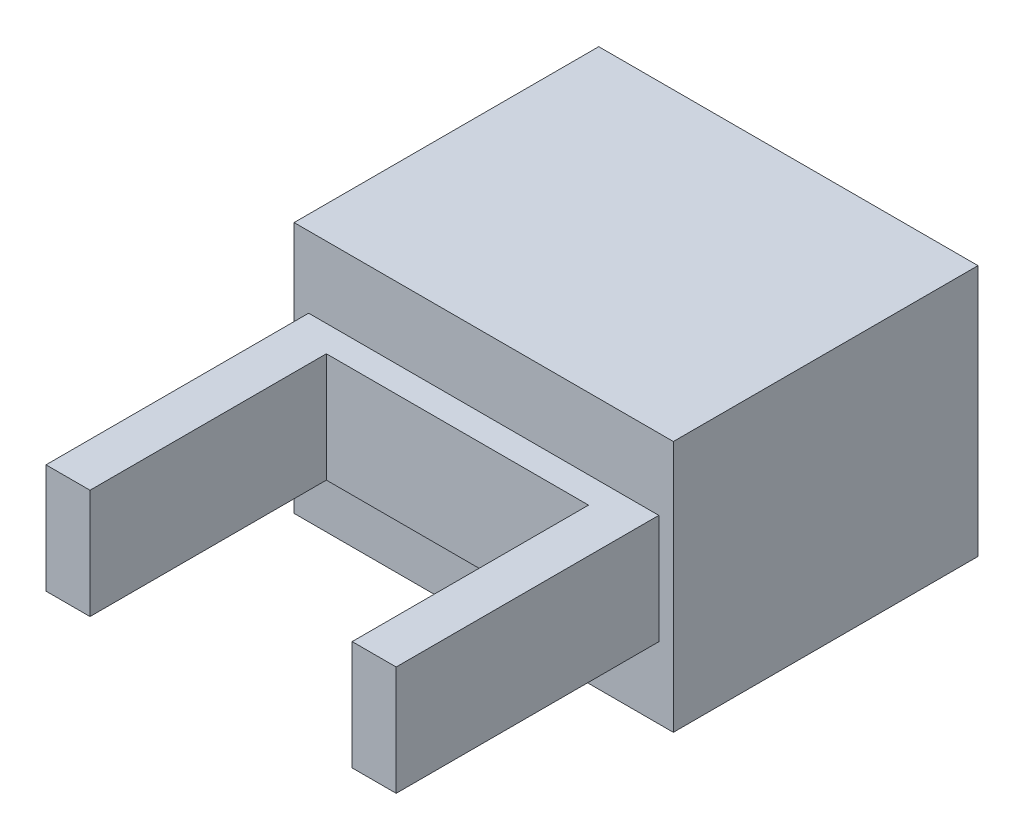
SolidWorks part; units mm, degrees
ref_plane "Front Plane" through (0, 0, 0) normal (0, 0, 1) x (1, 0, 0)
ref_plane "Top Plane" through (0, 0, 0) normal (0, 1, 0) x (1, 0, 0)
ref_plane "Right Plane" through (0, 0, 0) normal (1, 0, 0) x (0, 0, -1)
sketch "Sketch1" plane through (0, 0, 0) normal (0, 0, 1) x (1, 0, 0)
  line L1 (50.8, -15.875) -> (-50.8, -15.875)
  line L2 (50.8, -15.875) -> (50.8, 15.875)
  line L3 (50.8, 15.875) -> (-50.8, 15.875)
  line L4 (-50.8, -15.875) -> (-50.8, 15.875)
  line L5 (50.8, -15.875) -> (-50.8, 15.875) construction
  line L6 (50.8, 15.875) -> (-50.8, -15.875) construction
  point P0 (0, 0)
  dimension "D1" = 101.6
  dimension "D2" = 31.75
extrude "Boss-Extrude1" add sketch "Sketch1" along normal blind 76.2
sketch "Sketch2" plane through (0, 0, 76.2) normal (0, 0, 1) x (1, 0, 0)
  line L0 (50.8, 15.875) -> (-50.8, 15.875) construction
  line L1 (38.032, -15.875) -> (-38.032, -15.875)
  line L2 (38.032, -15.875) -> (38.032, 15.875)
  line L3 (38.032, 15.875) -> (-38.032, 15.875)
  line L4 (-38.032, -15.875) -> (-38.032, 15.875)
  line L5 (38.032, -15.875) -> (-38.032, 15.875) construction
  line L6 (38.032, 15.875) -> (-38.032, -15.875) construction
  point P0 (0, 0)
extrude "Cut-Extrude1" cut sketch "Sketch2" against normal offset from surface (68.58 mm away) 7.62 up to face at (0, 0, 0)
sketch "Sketch4" plane through (0, 0, 0) normal (0, 0, -1) x (-1, 0, 0)
  line L1 (55.018, -36.5406) -> (-55.018, -36.5406)
  line L2 (55.018, -36.5406) -> (55.018, 36.5406)
  line L3 (55.018, 36.5406) -> (-55.018, 36.5406)
  line L4 (-55.018, -36.5406) -> (-55.018, 36.5406)
  line L5 (55.018, -36.5406) -> (-55.018, 36.5406) construction
  line L6 (55.018, 36.5406) -> (-55.018, -36.5406) construction
  point P0 (0, 0)
extrude "Boss-Extrude2" add sketch "Sketch4" along normal blind 88.392 contours L1 L4 L3 L2
